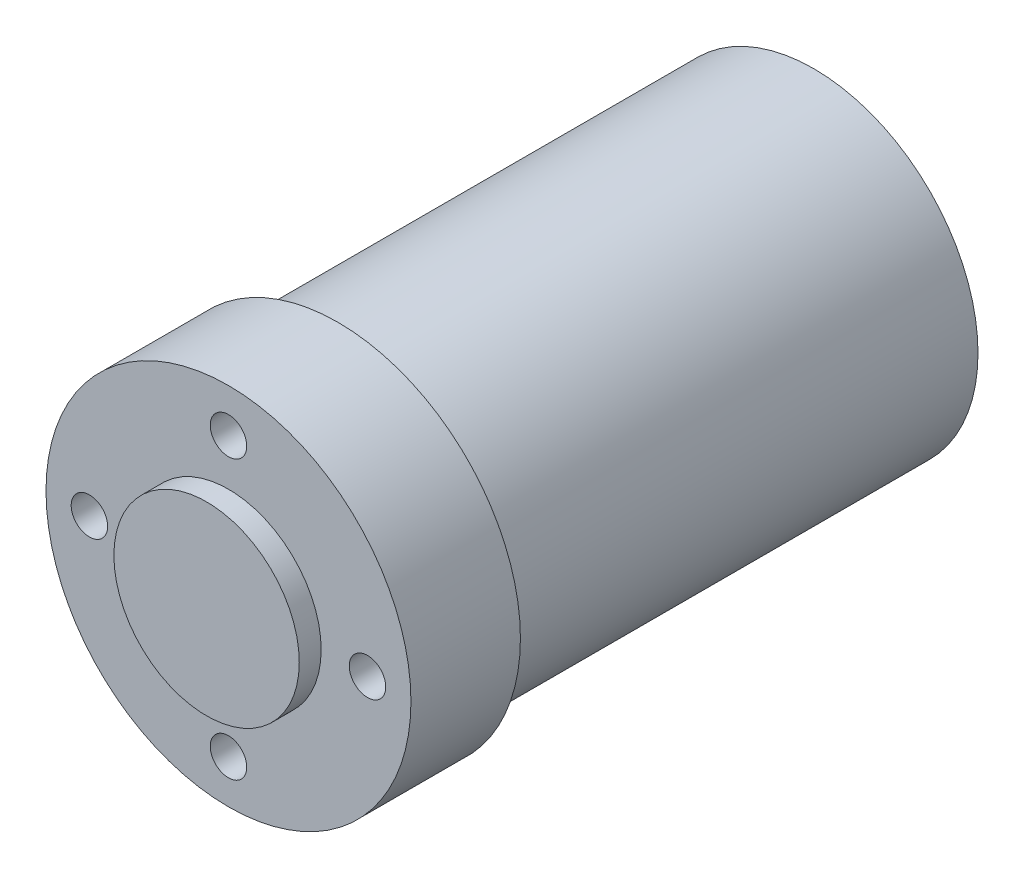
SolidWorks part; units mm, degrees
material "6061 Alloy"
ref_plane "Front" through (0, 0, 0) normal (0, 0, 1) x (1, 0, 0)
ref_plane "Top" through (0, 0, 0) normal (0, 1, 0) x (1, 0, 0)
ref_plane "Right" through (0, 0, 0) normal (1, 0, 0) x (0, 0, -1)
ref_plane "Plane1" through (0, 0, 0) normal (0, -1, 0) x (1, 0, 0)
sketch "Sketch1" plane through (0, 0, 0) normal (0, -1, 0) x (1, 0, 0)
  line L0 (25, 80) -> (0, 80)
  line L1 (0, 80) -> (0, 65)
  line L2 (0, 65) -> (25, 65)
  line L3 (25, 65) -> (25, 80)
  line L4 (0, 80) -> (0, 65) construction
revolve "Revolve1" add sketch "Sketch1" angle 360 about L4
sketch "Sketch2" plane through (0, 0, 80) normal (0, 0, 1) x (1, 0, 0)
  circle A0 centre (0, 0) radius 12.7
extrude "Boss-Extrude1" add sketch "Sketch2" along normal blind 3
sketch "Sketch3" plane through (0, 0, 65) normal (0, 0, -1) x (-1, 0, 0)
  circle A0 centre (0, 0) radius 22.4917
extrude "Boss-Extrude2" add sketch "Sketch3" along normal blind 65.2
hole_wizard "M6x1.0 Tapped Hole1" positions "Sketch5" profile "Sketch4" tap size "M6x1.0" standard "ANSI Metric"
sketch "Sketch5" plane through (0, 0, -0.2) normal (0, 0, -1) x (-1, 0, 0)
  point P0 (0, 17.5)
  point P1 (16.6435, 5.4078)
  point P2 (10.2862, -14.1578)
  point P3 (-10.2862, -14.1578)
  point P4 (-16.6435, 5.4078)
sketch "Sketch4" plane through (0, 17.5, -0.2) normal (1, 0, 0) x (0, 1, 0)
  line L0 (0, 0) -> (0, 11.5022)
  line L1 (0, 11.5022) -> (2.5, 10)
  line L2 (2.5, 10) -> (2.5, 0)
  line L5 (2.5, 0) -> (0, 0)
  line L10 (0, 11.5022) -> (-2.5, 10) construction
  line L11 (0, -6.35) -> (0, 107.95) construction
  dimension "Tap Drill Dia." = 5
  dimension "Tap Drill Depth" = 10
  dimension "Drill Angle" = 118
hole_wizard "M6x1.0 Tapped Hole2" positions "Sketch7" profile "Sketch6" tap size "M6x1.0" standard "ANSI Metric"
sketch "Sketch7" plane through (0, 0, 80) normal (0, 0, 1) x (1, 0, 0)
  point P0 (-19.05, 0)
  point P1 (0, -19.05)
  point P2 (19.05, 0)
  point P3 (0, 19.05)
sketch "Sketch6" plane through (-19.05, 0, 80) normal (1, 0, 0) x (0, -1, 0)
  line L0 (0, 0) -> (0, 16.5022)
  line L1 (0, 16.5022) -> (2.5, 15)
  line L2 (2.5, 15) -> (2.5, 0)
  line L5 (2.5, 0) -> (0, 0)
  line L10 (0, 16.5022) -> (-2.5, 15) construction
  line L11 (0, -6.35) -> (0, 107.95) construction
  dimension "Tap Drill Dia." = 5
  dimension "Tap Drill Depth" = 15
  dimension "Drill Angle" = 118
